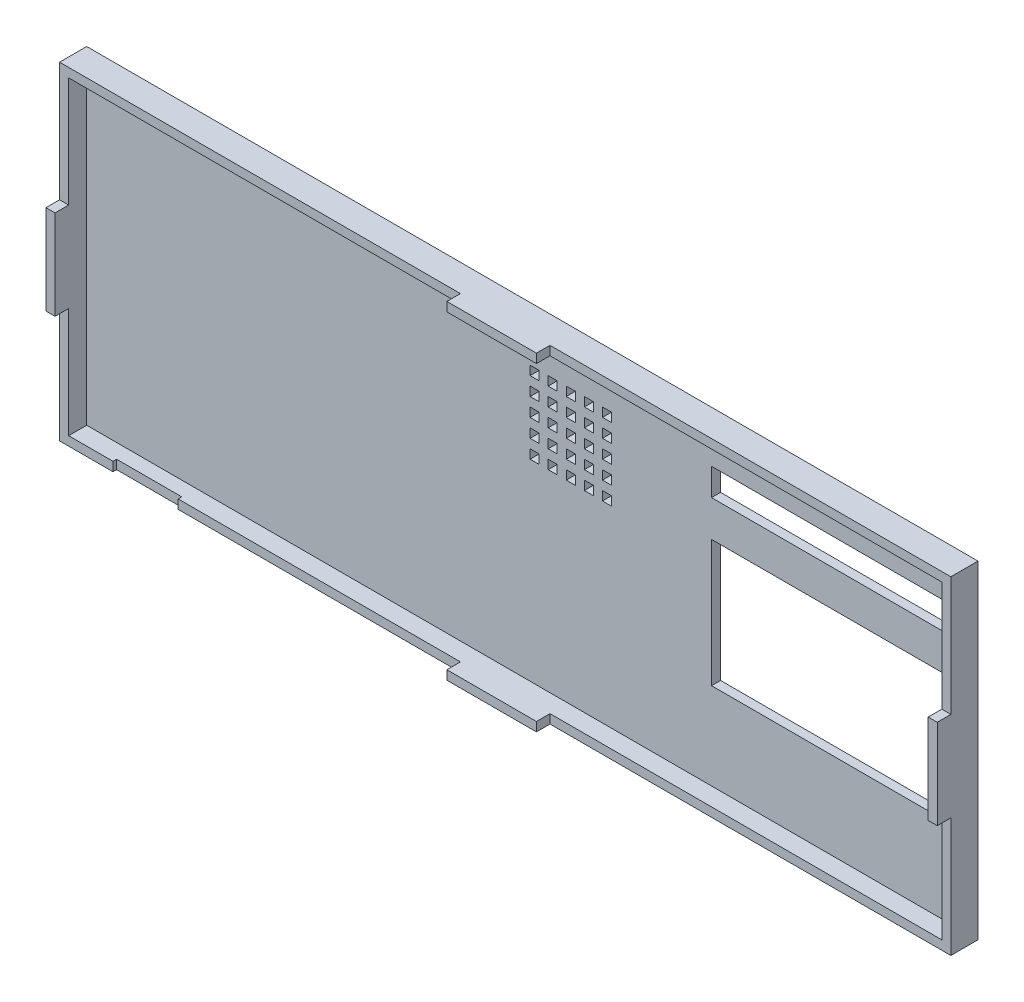
SolidWorks part; units mm, degrees
ref_plane "Alzado" through (0, 0, 0) normal (0, 0, 1) x (1, 0, 0)
ref_plane "Planta" through (0, 0, 0) normal (0, 1, 0) x (1, 0, 0)
ref_plane "Vista lateral" through (0, 0, 0) normal (1, 0, 0) x (0, 0, -1)
sketch "Croquis1" plane through (0, 0, 0) normal (0, 0, 1) x (1, 0, 0)
  line L1 (-57.701, 25.0424) -> (40.799, 25.0424)
  line L2 (-57.701, 25.0424) -> (-57.701, -11.2076)
  line L3 (-57.701, -11.2076) -> (40.799, -11.2076)
  line L4 (40.799, 25.0424) -> (40.799, -11.2076)
  dimension "D1" = 98.5
  dimension "D2" = 36.25
extrude "Saliente-Extruir1" add sketch "Croquis1" along normal blind 1
sketch "Croquis3" plane through (0, 0, 1) normal (0, 0, 1) x (1, 0, 0)
  line L0 (-57.701, 25.0424) -> (-57.701, -11.2076) construction
  line L1 (-56.701, 24.0424) -> (39.799, 24.0424)
  line L2 (-56.701, 24.0424) -> (-56.701, -10.2076)
  line L3 (-56.701, -10.2076) -> (39.799, -10.2076)
  line L4 (39.799, 24.0424) -> (39.799, -10.2076)
  line L5 (40.799, -11.2076) -> (40.799, 25.0424) construction
  line L6 (40.799, 25.0424) -> (-57.701, 25.0424) construction
  line L7 (-57.701, -11.2076) -> (40.799, -11.2076) construction
  line L9 (-57.701, 25.0424) -> (40.799, 25.0424)
  line L10 (-57.701, 25.0424) -> (-57.701, -11.2076)
  line L11 (-57.701, -11.2076) -> (40.799, -11.2076)
  line L12 (40.799, 25.0424) -> (40.799, -11.2076)
  dimension "D1" = 1
  dimension "D2" = 1
  dimension "D3" = 1
  dimension "D4" = 1
extrude "Saliente-Extruir2" add sketch "Croquis3" along normal blind 2
sketch "Croquis4" plane through (0, 0, 3) normal (0, 0, 1) x (1, 0, 0)
  line L0 (-57.701, 25.0424) -> (-57.701, -11.2076) construction
  line L1 (-57.701, 11.8674) -> (-56.701, 11.8674)
  line L3 (-57.701, 1.9674) -> (-56.701, 1.9674)
  line L6 (-13.401, 25.0424) -> (-13.401, 24.0424)
  line L8 (-3.501, 25.0424) -> (-3.501, 24.0424)
  line L9 (40.799, 25.0424) -> (-57.701, 25.0424) construction
  line L10 (-3.501, -10.2076) -> (-3.501, -11.2076)
  line L11 (-13.401, 25.0424) -> (-3.501, 25.0424)
  line L12 (-57.701, 11.8674) -> (-57.701, 1.9674)
  line L13 (-13.401, -11.2076) -> (-3.501, -11.2076)
  line L14 (40.799, 11.8674) -> (40.799, 1.9674)
  line L15 (-3.501, -10.2076) -> (-13.401, -10.2076)
  line L16 (39.799, 1.9674) -> (39.799, 11.8674)
  line L17 (-3.501, 24.0424) -> (-13.401, 24.0424)
  line L18 (-56.701, 1.9674) -> (-56.701, 11.8674)
  line L19 (-13.401, -10.2076) -> (-13.401, -11.2076)
  line L24 (39.799, 11.8674) -> (40.799, 11.8674)
  line L25 (39.799, 1.9674) -> (40.799, 1.9674)
  point P11 (-57.701, 6.9174)
  point P15 (-8.451, 25.0424)
extrude "Saliente-Extruir3" add sketch "Croquis4" along normal blind 1.5
sketch "Croquis6" plane through (0, 0, 3) normal (0, 0, 1) x (1, 0, 0)
  line L0 (-56.701, -10.2076) -> (39.799, -10.2076) construction
  line L1 (-51.801, -10.2076) -> (-44.601, -10.2076)
  line L2 (-51.801, -10.2076) -> (-51.801, -11.2076)
  line L3 (-51.801, -11.2076) -> (-44.601, -11.2076)
  line L4 (-44.601, -10.2076) -> (-44.601, -11.2076)
  line L5 (-57.701, -11.2076) -> (-13.401, -11.2076) construction
  line L6 (-57.701, 1.9674) -> (-57.701, -11.2076) construction
  dimension "D1" = 5.9
  dimension "D2" = 13.1
extrude "Cortar-Extruir1" cut sketch "Croquis6" against normal blind 0.4
sketch "Croquis8" plane through (0, 0, 1) normal (0, 0, 1) x (1, 0, 0)
  line L6 (12.349, 13.3924) -> (38.799, 13.3924)
  line L7 (12.349, 13.3924) -> (12.349, -0.6076)
  line L8 (12.349, -0.6076) -> (38.799, -0.6076)
  line L9 (38.799, 13.3924) -> (38.799, -0.6076)
  line L10 (-3.501, -11.2076) -> (40.799, -11.2076) construction
  line L11 (39.799, 11.8674) -> (39.799, 1.9674) construction
  line L12 (-56.701, -10.2076) -> (39.799, -10.2076) construction
  dimension "D1" = 10.6
  dimension "D2" = 1
  dimension "D3" = 26.45
  dimension "D4" = 23.6
extrude "Cortar-Extruir2" cut sketch "Croquis8" against normal blind 30.4
sketch "Croquis10" plane through (0, 0, 0) normal (0, 0, -1) x (-1, 0, 0)
  line L0 (-38.799, 13.3924) -> (-12.349, 13.3924) construction
  line L5 (-38.799, 20.3924) -> (-12.349, 20.3924)
  line L6 (-38.799, 20.3924) -> (-38.799, 17.3924)
  line L7 (-38.799, 17.3924) -> (-12.349, 17.3924)
  line L8 (-12.349, 20.3924) -> (-12.349, 17.3924)
  dimension "D1" = 3
  dimension "D2" = 4
extrude "Cortar-Extruir3" cut sketch "Croquis10" against normal blind 30.4
sketch "Croquis11" plane through (0, 0, 0) normal (0, 0, -1) x (-1, 0, 0)
  line L0 (-40.799, -11.2076) -> (-40.799, 25.0424) construction
  line L2 (-1.299, 20.0424) -> (-1.299, 19.0424)
  line L3 (-1.299, 11.0424) -> (-0.299, 11.0424)
  line L5 (-40.799, 25.0424) -> (57.701, 25.0424) construction
  line L6 (7.701, 20.0424) -> (7.701, 19.0424)
  line L7 (6.701, 20.0424) -> (6.701, 19.0424)
  line L8 (5.701, 20.0424) -> (5.701, 19.0424)
  line L9 (4.701, 20.0424) -> (4.701, 19.0424)
  line L10 (2.701, 20.0424) -> (2.701, 19.0424)
  line L11 (3.701, 20.0424) -> (3.701, 19.0424)
  line L12 (1.701, 20.0424) -> (1.701, 19.0424)
  line L13 (0.701, 20.0424) -> (0.701, 19.0424)
  line L14 (-0.299, 20.0424) -> (-0.299, 19.0424)
  line L15 (-1.299, 20.0424) -> (-0.299, 20.0424)
  line L16 (-1.299, 19.0424) -> (-0.299, 19.0424)
  line L17 (-1.299, 18.0424) -> (-0.299, 18.0424)
  line L18 (-1.299, 17.0424) -> (-0.299, 17.0424)
  line L19 (-1.299, 16.0424) -> (-0.299, 16.0424)
  line L20 (-1.299, 15.0424) -> (-0.299, 15.0424)
  line L21 (-1.299, 14.0424) -> (-0.299, 14.0424)
  line L22 (-1.299, 13.0424) -> (-0.299, 13.0424)
  line L23 (-1.299, 12.0424) -> (-0.299, 12.0424)
  line L25 (0.701, 20.0424) -> (1.701, 20.0424)
  line L26 (0.701, 19.0424) -> (1.701, 19.0424)
  line L27 (0.701, 18.0424) -> (1.701, 18.0424)
  line L28 (0.701, 17.0424) -> (1.701, 17.0424)
  line L29 (0.701, 16.0424) -> (1.701, 16.0424)
  line L30 (0.701, 15.0424) -> (1.701, 15.0424)
  line L31 (0.701, 14.0424) -> (1.701, 14.0424)
  line L32 (0.701, 13.0424) -> (1.701, 13.0424)
  line L33 (0.701, 12.0424) -> (1.701, 12.0424)
  line L34 (0.701, 11.0424) -> (1.701, 11.0424)
  line L35 (2.701, 11.0424) -> (3.701, 11.0424)
  line L36 (2.701, 12.0424) -> (3.701, 12.0424)
  line L37 (2.701, 13.0424) -> (3.701, 13.0424)
  line L38 (2.701, 14.0424) -> (3.701, 14.0424)
  line L39 (2.701, 15.0424) -> (3.701, 15.0424)
  line L40 (2.701, 16.0424) -> (3.701, 16.0424)
  line L41 (2.701, 17.0424) -> (3.701, 17.0424)
  line L42 (2.701, 18.0424) -> (3.701, 18.0424)
  line L43 (2.701, 19.0424) -> (3.701, 19.0424)
  line L44 (2.701, 20.0424) -> (3.701, 20.0424)
  line L47 (4.701, 20.0424) -> (5.701, 20.0424)
  line L48 (4.701, 19.0424) -> (5.701, 19.0424)
  line L49 (4.701, 18.0424) -> (5.701, 18.0424)
  line L50 (4.701, 17.0424) -> (5.701, 17.0424)
  line L51 (4.701, 16.0424) -> (5.701, 16.0424)
  line L52 (4.701, 15.0424) -> (5.701, 15.0424)
  line L53 (4.701, 14.0424) -> (5.701, 14.0424)
  line L54 (4.701, 13.0424) -> (5.701, 13.0424)
  line L55 (4.701, 12.0424) -> (5.701, 12.0424)
  line L56 (4.701, 11.0424) -> (5.701, 11.0424)
  line L57 (6.701, 11.0424) -> (7.701, 11.0424)
  line L58 (6.701, 12.0424) -> (7.701, 12.0424)
  line L59 (6.701, 13.0424) -> (7.701, 13.0424)
  line L60 (6.701, 14.0424) -> (7.701, 14.0424)
  line L61 (6.701, 15.0424) -> (7.701, 15.0424)
  line L62 (6.701, 16.0424) -> (7.701, 16.0424)
  line L63 (6.701, 17.0424) -> (7.701, 17.0424)
  line L64 (6.701, 18.0424) -> (7.701, 18.0424)
  line L65 (6.701, 19.0424) -> (7.701, 19.0424)
  line L66 (6.701, 20.0424) -> (7.701, 20.0424)
  line L68 (7.701, 12.0424) -> (7.701, 11.0424)
  line L69 (6.701, 12.0424) -> (6.701, 11.0424)
  line L70 (5.701, 12.0424) -> (5.701, 11.0424)
  line L71 (4.701, 12.0424) -> (4.701, 11.0424)
  line L72 (3.701, 12.0424) -> (3.701, 11.0424)
  line L73 (2.701, 12.0424) -> (2.701, 11.0424)
  line L74 (1.701, 12.0424) -> (1.701, 11.0424)
  line L75 (0.701, 12.0424) -> (0.701, 11.0424)
  line L76 (-0.299, 12.0424) -> (-0.299, 11.0424)
  line L77 (-1.299, 12.0424) -> (-1.299, 11.0424)
  line L78 (-1.299, 14.0424) -> (-1.299, 13.0424)
  line L79 (-0.299, 14.0424) -> (-0.299, 13.0424)
  line L80 (0.701, 14.0424) -> (0.701, 13.0424)
  line L81 (1.701, 14.0424) -> (1.701, 13.0424)
  line L82 (2.701, 14.0424) -> (2.701, 13.0424)
  line L83 (3.701, 14.0424) -> (3.701, 13.0424)
  line L84 (4.701, 14.0424) -> (4.701, 13.0424)
  line L85 (5.701, 14.0424) -> (5.701, 13.0424)
  line L86 (6.701, 14.0424) -> (6.701, 13.0424)
  line L87 (7.701, 14.0424) -> (7.701, 13.0424)
  line L88 (7.701, 16.0424) -> (7.701, 15.0424)
  line L89 (6.701, 16.0424) -> (6.701, 15.0424)
  line L90 (5.701, 16.0424) -> (5.701, 15.0424)
  line L91 (4.701, 16.0424) -> (4.701, 15.0424)
  line L92 (3.701, 16.0424) -> (3.701, 15.0424)
  line L93 (2.701, 16.0424) -> (2.701, 15.0424)
  line L94 (1.701, 16.0424) -> (1.701, 15.0424)
  line L95 (0.701, 16.0424) -> (0.701, 15.0424)
  line L96 (-0.299, 16.0424) -> (-0.299, 15.0424)
  line L97 (-1.299, 16.0424) -> (-1.299, 15.0424)
  line L98 (-1.299, 18.0424) -> (-1.299, 17.0424)
  line L99 (-0.299, 18.0424) -> (-0.299, 17.0424)
  line L100 (0.701, 18.0424) -> (0.701, 17.0424)
  line L101 (1.701, 18.0424) -> (1.701, 17.0424)
  line L102 (2.701, 18.0424) -> (2.701, 17.0424)
  line L103 (3.701, 18.0424) -> (3.701, 17.0424)
  line L104 (4.701, 18.0424) -> (4.701, 17.0424)
  line L105 (5.701, 18.0424) -> (5.701, 17.0424)
  line L106 (6.701, 18.0424) -> (6.701, 17.0424)
  line L107 (7.701, 18.0424) -> (7.701, 17.0424)
  dimension "D1" = 39.5
  dimension "D4" = 14
  dimension "D6" = 1
  dimension "D7" = 1
  dimension "D8" = 1
  dimension "D9" = 1
  dimension "D10" = 1
  dimension "D11" = 1
  dimension "D12" = 1
  dimension "D13" = 1
  dimension "D15" = 1
  dimension "D16" = 1
  dimension "D17" = 1
  dimension "D18" = 1
  dimension "D19" = 1
  dimension "D20" = 1
  dimension "D21" = 1
  dimension "D22" = 1
extrude "Cortar-Extruir4" cut sketch "Croquis11" against normal blind 30.4
sketch "Croquis13" plane through (0, 0, 0) normal (0, 0, -1) x (-1, 0, 0)
  text T0 "HUDuino" font "Century Gothic" height in points 44
extrude "Cortar-Extruir5" cut sketch "Croquis13" against normal blind 0.5
